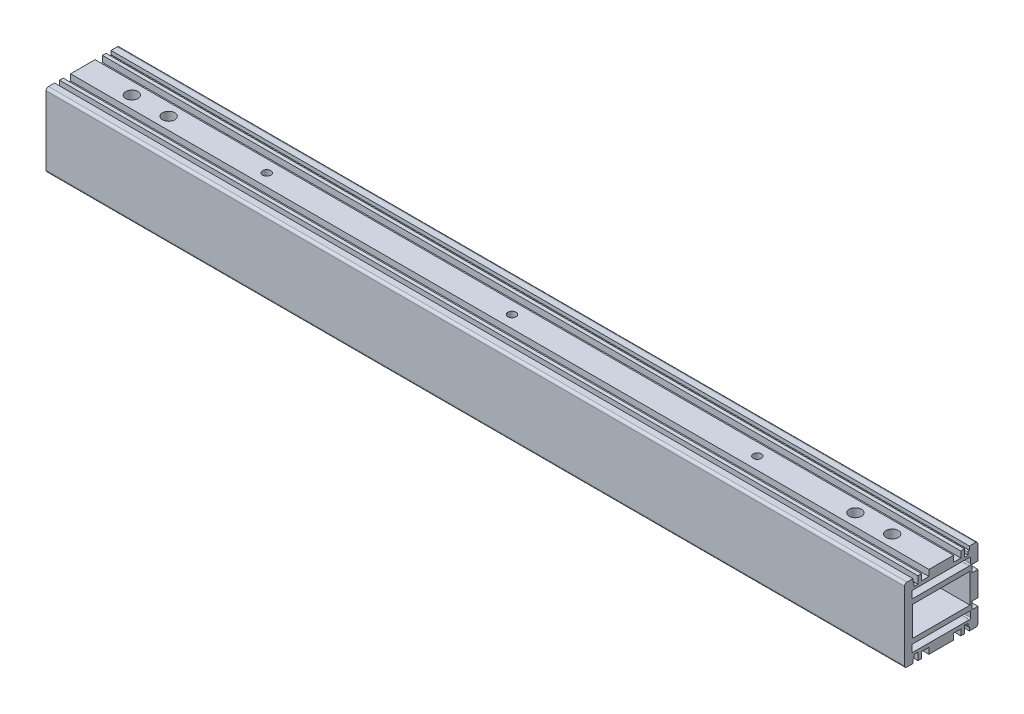
SolidWorks part; units mm, degrees
ref_plane "前视基准面" through (0, 0, 0) normal (0, 0, 1) x (1, 0, 0)
ref_plane "上视基准面" through (0, 0, 0) normal (0, 1, 0) x (1, 0, 0)
ref_plane "右视基准面" through (0, 0, 0) normal (1, 0, 0) x (0, 0, -1)
sketch "草图1" plane through (0, 0, 0) normal (1, 0, 0) x (0, 0, -1)
  line L0 (-15, 15) -> (15, -15) construction
  line L1 (-14, 15) -> (-11.5, 15)
  line L2 (-15, 14) -> (-15, -14)
  line L3 (-14, -15) -> (-11.5, -15)
  line L4 (15, 14) -> (15, 8)
  line L5 (15, 15) -> (-15, -15) construction
  line L6 (-11.5, 15) -> (-11.5, 13.5)
  line L7 (-11.5, 13.5) -> (-11.4, 13.5)
  line L8 (-11, 13.1) -> (-11, 12)
  line L9 (-11, 12) -> (-9.5, 12)
  line L10 (-9.5, 12) -> (-9.5, 15)
  line L11 (-9.5, 15) -> (-8, 15)
  line L12 (-8, 15) -> (-8, 12.5)
  line L13 (-8, 12.5) -> (-5, 12.5)
  line L14 (-5, 12.5) -> (-5, 15)
  line L15 (-5, 15) -> (5, 15)
  line L16 (0, 21.5201) -> (0, -18.309) construction
  line L17 (0, 55) -> (0, -55) construction
  line L18 (5, 12.5) -> (5, 15)
  line L19 (8, 12.5) -> (5, 12.5)
  line L20 (8, 15) -> (8, 12.5)
  line L21 (9.5, 15) -> (8, 15)
  line L22 (9.5, 12) -> (9.5, 15)
  line L23 (11, 12) -> (9.5, 12)
  line L24 (11, 13.1) -> (11, 12)
  line L25 (11.5, 13.5) -> (11.4, 13.5)
  line L26 (11.5, 15) -> (11.5, 13.5)
  line L27 (8, 15) -> (9.5, 15)
  line L28 (11.5, 15) -> (14, 15)
  line L29 (-19.8303, 0) -> (22.13, 0) construction
  line L30 (55, 0) -> (-55, 0) construction
  line L31 (8, -15) -> (9.5, -15)
  line L32 (11.5, -15) -> (11.5, -13.5)
  line L33 (11.5, -13.5) -> (11.4, -13.5)
  line L34 (11, -13.1) -> (11, -12)
  line L35 (11, -12) -> (9.5, -12)
  line L36 (9.5, -12) -> (9.5, -15)
  line L37 (9.5, -15) -> (8, -15)
  line L38 (8, -15) -> (8, -12.5)
  line L39 (8, -12.5) -> (5, -12.5)
  line L40 (5, -12.5) -> (5, -15)
  line L41 (-5, -15) -> (5, -15)
  line L42 (-5, -12.5) -> (-5, -15)
  line L43 (-8, -12.5) -> (-5, -12.5)
  line L44 (-8, -15) -> (-8, -12.5)
  line L45 (-9.5, -15) -> (-8, -15)
  line L46 (-9.5, -12) -> (-9.5, -15)
  line L47 (-11, -12) -> (-9.5, -12)
  line L48 (-11, -13.1) -> (-11, -12)
  line L49 (-11.5, -13.5) -> (-11.4, -13.5)
  line L50 (-11.5, -15) -> (-11.5, -13.5)
  line L51 (-9.5, -15) -> (-8, -15)
  line L52 (-5, -15) -> (5, -15)
  line L53 (8, -15) -> (9.5, -15)
  line L54 (11.5, -15) -> (14, -15)
  line L55 (15, 8) -> (12.5, 8)
  line L56 (12.5, 8) -> (12.5, 5)
  line L57 (12.5, 5) -> (15, 5)
  line L58 (12.5, -5) -> (15, -5)
  line L59 (12.5, -8) -> (12.5, -5)
  line L60 (15, -8) -> (12.5, -8)
  line L61 (15, 5) -> (15, -5)
  line L62 (15, -8) -> (15, -14)
  line L63 (12, -10.5) -> (12, -8.5)
  line L64 (-11.5, 11) -> (11.5, 11)
  line L65 (-12, 10.5) -> (-12, 8.5)
  line L66 (-11.5, 8) -> (11.5, 8)
  line L67 (12, 10.5) -> (12, 8.5)
  line L68 (-11.5, -8) -> (11.5, -8)
  line L69 (-12, -10.5) -> (-12, -8.5)
  line L70 (-11.5, -11) -> (11.5, -11)
  line L72 (-11.75, 6) -> (11.75, 6)
  line L73 (-11.75, 6) -> (-11.75, -6)
  line L74 (-11.75, -6) -> (11.75, -6)
  line L75 (11.75, 6) -> (11.75, -6)
  arc A0 (12, 8.5) -> (11.5, 8) centre (11.5, 8.5) cw
  arc A1 (11.5, 11) -> (12, 10.5) centre (11.5, 10.5) cw
  arc A2 (-11.5, 11) -> (-12, 10.5) centre (-11.5, 10.5) ccw
  arc A3 (-11.5, 8) -> (-12, 8.5) centre (-11.5, 8.5) cw
  arc A4 (-11, -13.1) -> (-11.4, -13.5) centre (-11.4, -13.1) cw
  arc A5 (11.4, -13.5) -> (11, -13.1) centre (11.4, -13.1) cw
  arc A6 (11.4, 13.5) -> (11, 13.1) centre (11.4, 13.1) ccw
  arc A7 (-11, 13.1) -> (-11.4, 13.5) centre (-11.4, 13.1) ccw
  arc A8 (-11.5, -8) -> (-12, -8.5) centre (-11.5, -8.5) ccw
  arc A9 (-11.5, -11) -> (-12, -10.5) centre (-11.5, -10.5) cw
  arc A10 (11.5, -11) -> (12, -10.5) centre (11.5, -10.5) ccw
  arc A11 (12, -8.5) -> (11.5, -8) centre (11.5, -8.5) ccw
  arc A12 (14, 15) -> (15, 14) centre (14, 14) cw
  arc A13 (14, -15) -> (15, -14) centre (14, -14) ccw
  arc A14 (-15, -14) -> (-14, -15) centre (-14, -14) ccw
  arc A15 (-15, 14) -> (-14, 15) centre (-14, 14) cw
  point P69 (12, 11)
  point P72 (-12, 11)
  point P77 (-11, -13.5)
  point P80 (11, -13.5)
  point P83 (11, 13.5)
  point P86 (-11, 13.5)
  point P99 (-12, -11)
  point P100 (12, -11)
  dimension "D17" = 0.5
  dimension "D18" = 0.4
  dimension "D21" = 1
  dimension "D1" = 3.5
  dimension "D2" = 1.5
  dimension "D3" = 0.5
  dimension "D4" = 1.5
  dimension "D5" = 3
  dimension "D6" = 30
  dimension "D7" = 30
  dimension "D8" = 1.5
  dimension "D9" = 2.5
  dimension "D10" = 3
  dimension "D11" = 2.5
  dimension "D12" = 7
  dimension "D13" = 3
  dimension "D14" = 4
  dimension "D15" = 3
  dimension "D16" = 24
  dimension "D19" = 23.5
  dimension "D20" = 12
extrude "凸台-拉伸1" add sketch "草图1" along normal mid plane 350 contours A15 L2 A14 L3 L50 L49 A4 L48 L47 L46 L45 L44 L43 L42 L41 L40 L39 L38 L31 L36 L35 L34 A5 L33 L32 L54 A13 L62 L60 L59 L58 L61 L57 L56 L55 L4 A12 L28 L26 L25 A6 L24 L23 L22 L21 L20 L19 L18 L15 L14 L13
hole_wizard "M6 螺纹孔1" positions "草图3" profile "草图2" tap size "M6" standard "GB"
sketch "草图3" plane through (0, -15, 0) normal (0, -1, 0) x (1, 0, 0)
  line L0 (-175, 5) -> (-175, -5) construction
  line L1 (175, -15) -> (-175, -15) construction
  point P0 (-155, 0)
  point P1 (-140, 0)
  point P4 (155, 0)
  point P7 (140, 0)
  dimension "D1" = 20
  dimension "D2" = 15
sketch "草图2" plane through (-155, -15, 0) normal (1, 0, 0) x (0, 0, -1)
  line L0 (0, 0) -> (0, 16.5022)
  line L1 (0, 16.5022) -> (2.5, 15)
  line L2 (2.5, 15) -> (2.5, 0)
  line L5 (2.5, 0) -> (0, 0)
  line L10 (0, 16.5022) -> (-2.5, 15) construction
  line L11 (0, -6.35) -> (0, 107.95) construction
  dimension "螺纹孔钻头直径" = 5
  dimension "螺纹孔钻头深度" = 15
  dimension "导头角度" = 118
cosmetic thread "孔螺蚊线1" parameters "D1"=9, "D2"=6
cosmetic thread "孔螺蚊线2" parameters "D1"=9, "D2"=6
cosmetic thread "孔螺蚊线3" parameters "D1"=9, "D2"=6
cosmetic thread "孔螺蚊线4" parameters "D1"=9, "D2"=6
hole_wizard "M6 螺纹孔2" positions "草图5" profile "草图4" tap size "M6" standard "GB"
sketch "草图5" plane through (0, 15, 0) normal (0, 1, 0) x (-1, 0, 0)
  line L0 (175, 5) -> (175, -5) construction
  line L1 (-175, 15) -> (175, 15) construction
  point P0 (155, 0)
  point P1 (140, 0)
  point P4 (-155, 0)
  point P7 (-140, 0)
  dimension "D1" = 20
  dimension "D2" = 15
sketch "草图4" plane through (-155, 15, 0) normal (1, 0, 0) x (0, 0, 1)
  line L0 (0, 0) -> (0, 16.5022)
  line L1 (0, 16.5022) -> (2.5, 15)
  line L2 (2.5, 15) -> (2.5, 0)
  line L5 (2.5, 0) -> (0, 0)
  line L10 (0, 16.5022) -> (-2.5, 15) construction
  line L11 (0, -6.35) -> (0, 107.95) construction
  dimension "螺纹孔钻头直径" = 5
  dimension "螺纹孔钻头深度" = 15
  dimension "导头角度" = 118
cosmetic thread "孔螺蚊线5" parameters "D1"=9, "D2"=6
cosmetic thread "孔螺蚊线6" parameters "D1"=9, "D2"=6
cosmetic thread "孔螺蚊线7" parameters "D1"=9, "D2"=6
cosmetic thread "孔螺蚊线8" parameters "D1"=9, "D2"=6
hole_wizard "M4 螺纹孔1" positions "草图9" profile "草图8" tap size "M4" standard "GB"
sketch "草图9" plane through (0, 15, 0) normal (0, 1, 0) x (-1, 0, 0)
  line L0 (-175, 15) -> (175, 15) construction
  line L1 (175, 14) -> (175, 11.5) construction
  point P0 (100, 0)
  point P1 (0, 0)
  point P4 (-100, 0)
  dimension "D1" = 15
  dimension "D2" = 75
  dimension "D3" = 100
sketch "草图8" plane through (-100, 15, 0) normal (1, 0, 0) x (0, 0, 1)
  line L0 (0, 0) -> (0, 11.0914)
  line L1 (0, 11.0914) -> (1.65, 10.1)
  line L2 (1.65, 10.1) -> (1.65, 0)
  line L5 (1.65, 0) -> (0, 0)
  line L10 (0, 11.0914) -> (-1.65, 10.1) construction
  line L11 (0, -6.35) -> (0, 107.95) construction
  dimension "螺纹孔钻头直径" = 3.3
  dimension "螺纹孔钻头深度" = 10.1
  dimension "导头角度" = 118
cosmetic thread "孔螺蚊线9" parameters "D1"=8, "D2"=4
cosmetic thread "孔螺蚊线10" parameters "D1"=8, "D2"=4
cosmetic thread "孔螺蚊线11" parameters "D1"=8, "D2"=4
hole_wizard "M6 螺纹孔3" positions "草图11" profile "草图10" tap size "M6" standard "GB"
sketch "草图11" plane through (0, -15, 0) normal (0, -1, 0) x (1, 0, 0)
  line L0 (175, -15) -> (-175, -15) construction
  line L1 (-175, -11.5) -> (-175, -14) construction
  line L2 (175, 14) -> (175, 11.5) construction
  point P0 (-105, 0)
  point P1 (105, 0)
  dimension "D1" = 15
  dimension "D2" = 70
  dimension "D3" = 15
  dimension "D4" = 70
sketch "草图10" plane through (-105, -15, 0) normal (1, 0, 0) x (0, 0, -1)
  line L0 (0, 0) -> (0, 16.5022)
  line L1 (0, 16.5022) -> (2.5, 15)
  line L2 (2.5, 15) -> (2.5, 0)
  line L5 (2.5, 0) -> (0, 0)
  line L10 (0, 16.5022) -> (-2.5, 15) construction
  line L11 (0, -6.35) -> (0, 107.95) construction
  dimension "螺纹孔钻头直径" = 5
  dimension "螺纹孔钻头深度" = 15
  dimension "导头角度" = 118
cosmetic thread "孔螺蚊线12" parameters "D1"=9, "D2"=6
cosmetic thread "孔螺蚊线13" parameters "D1"=9, "D2"=6
